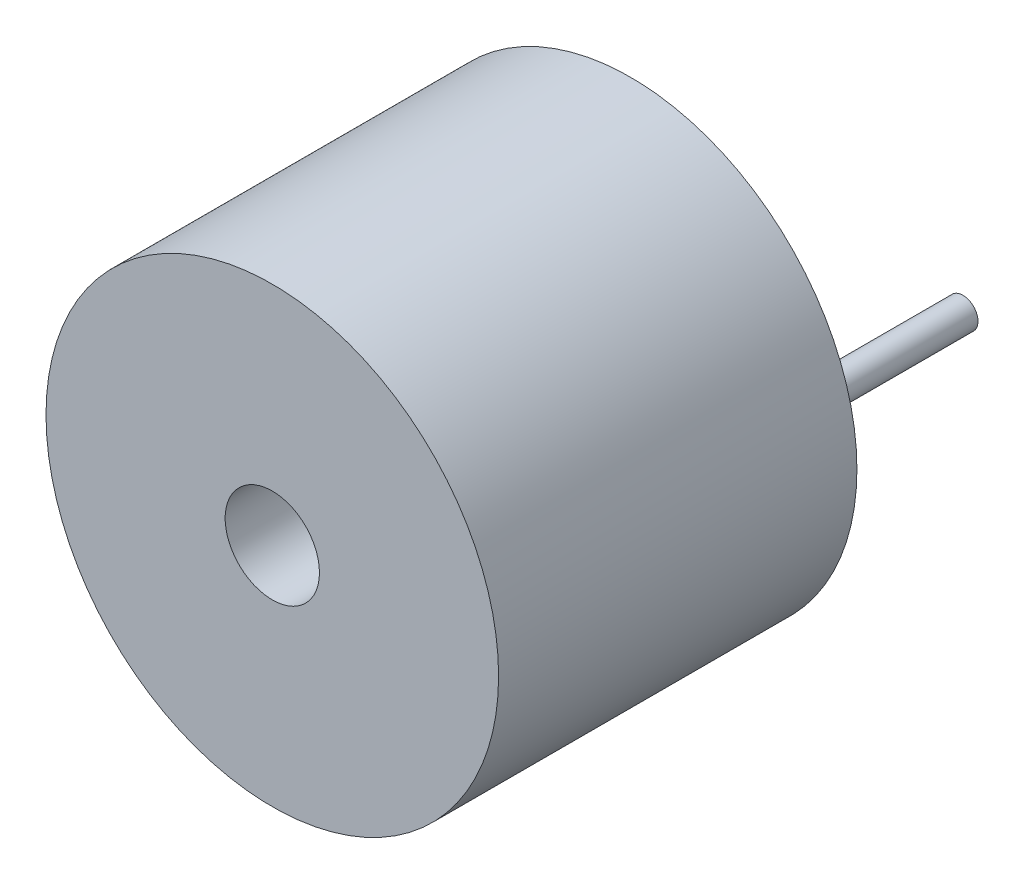
SolidWorks part; units mm, degrees
ref_plane "前视基准面" through (0, 0, 0) normal (0, 0, 1) x (1, 0, 0)
ref_plane "上视基准面" through (0, 0, 0) normal (0, 1, 0) x (1, 0, 0)
ref_plane "右视基准面" through (0, 0, 0) normal (1, 0, 0) x (0, 0, -1)
sketch "草图1" plane through (0, 0, 0) normal (0, 0, 1) x (1, 0, 0)
  circle A0 centre (0, 0) radius 6
  dimension "D1" = 12
extrude "拉伸1" add sketch "草图1" along normal blind 9.5
sketch "草图2" plane through (0, 0, 0) normal (0, 0, -1) x (-1, 0, 0)
  line L0 (6.6594, 0) -> (-8.124, 0) construction
  line L1 (0, 6.6022) -> (0, -6.3733) construction
  circle A0 centre (-3.81, 0) radius 0.4
  circle A1 centre (3.81, 0) radius 0.4
  dimension "D1" = 0.8
  dimension "D2" = 7.62
extrude "拉伸2" add sketch "草图2" along normal blind 5
sketch "草图3" plane through (0, 0, 9.5) normal (0, 0, 1) x (1, 0, 0)
  circle A0 centre (0, 0) radius 1.25
  dimension "D1" = 2.5
extrude "切除-拉伸1" cut sketch "草图3" against normal blind 5
